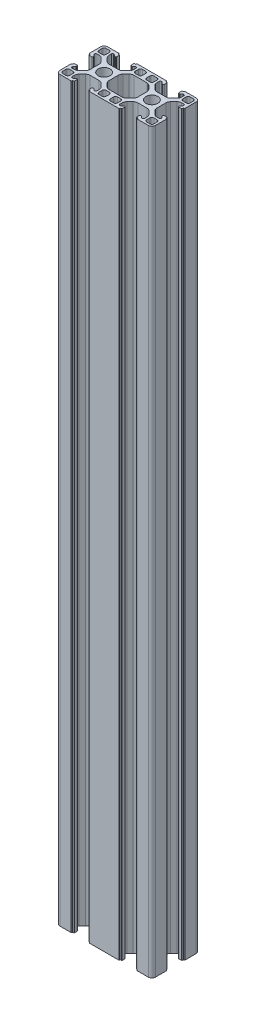
SolidWorks part; units mm, degrees
ref_plane "Спереди" through (0, 0, 0) normal (0, 0, 1) x (1, 0, 0)
ref_plane "Сверху" through (0, 0, 0) normal (0, 1, 0) x (1, 0, 0)
ref_plane "Справа" through (0, 0, 0) normal (1, 0, 0) x (0, 0, -1)
sketch "Эскиз1" plane through (0, 0, 0) normal (0, 1, 0) x (1, 0, 0)
  line L0 (-3.1522, 8.2837) -> (-1.6522, 6.7837) construction
  line L1 (18.3478, 9.7837) -> (15.3478, 6.7837) construction
  line L2 (-10.7522, 0.6837) -> (-0.7522, 10.6837) construction
  line L3 (9.2478, 4.6837) -> (11.1466, 4.6837)
  line L4 (9.2478, 0.6837) -> (19.2478, 10.6837) construction
  line L5 (16.8478, 8.2837) -> (15.3478, 9.7837) construction
  line L6 (12.5608, 5.2695) -> (13.862, 6.5707)
  line L7 (16.1478, 6.7837) -> (17.5478, 6.7837)
  line L8 (15.3478, 7.5837) -> (15.3478, 8.9837)
  line L9 (17.5478, 9.7837) -> (16.1478, 9.7837)
  line L10 (14.4478, 8.8837) -> (14.4478, 7.9849)
  line L11 (13.011, 8.757) -> (13.4914, 9.2373)
  line L12 (12.4478, 10.2328) -> (12.9478, 10.2328)
  line L13 (12.8343, 8.6837) -> (12.5478, 8.6837)
  line L14 (13.8449, 9.3837) -> (13.9478, 9.3837)
  line L15 (12.9478, 10.5337) -> (12.9478, 10.2328)
  line L16 (12.2978, 10.0828) -> (12.2978, 8.9337)
  line L17 (17.7478, 10.6837) -> (13.0978, 10.6837)
  line L18 (18.3478, 8.9837) -> (18.3478, 7.5837)
  line L19 (19.2478, 9.1837) -> (19.2478, 4.5337)
  line L20 (18.6469, 3.7337) -> (17.4978, 3.7337)
  line L21 (19.0978, 4.3837) -> (18.7969, 4.3837)
  line L22 (17.9478, 5.2808) -> (17.9478, 5.3837)
  line L23 (17.2478, 4.2702) -> (17.2478, 3.9837)
  line L24 (18.7969, 3.8837) -> (18.7969, 4.3837)
  line L25 (17.321, 4.447) -> (17.8014, 4.9273)
  line L26 (17.4478, 5.8837) -> (16.549, 5.8837)
  line L27 (13.8336, 3.9967) -> (15.1348, 5.2979)
  line L28 (13.2478, 0.6837) -> (13.2478, 2.5825)
  line L29 (13.2478, 0.6837) -> (13.2478, -1.2151)
  line L30 (13.8336, -2.6293) -> (15.1348, -3.9305)
  line L31 (15.3478, -6.2163) -> (15.3478, -7.6163)
  line L32 (16.1478, -5.4163) -> (17.5478, -5.4163)
  line L33 (18.3478, -7.6163) -> (18.3478, -6.2163)
  line L34 (17.4478, -4.5163) -> (16.549, -4.5163)
  line L35 (17.321, -3.0795) -> (17.8014, -3.5598)
  line L36 (18.7969, -2.5163) -> (18.7969, -3.0163)
  line L37 (17.2478, -2.9027) -> (17.2478, -2.6163)
  line L38 (17.9478, -3.9134) -> (17.9478, -4.0163)
  line L39 (19.0978, -3.0163) -> (18.7969, -3.0163)
  line L40 (18.6469, -2.3663) -> (17.4978, -2.3663)
  line L41 (19.2478, -7.8163) -> (19.2478, -3.1663)
  line L42 (17.5478, -8.4163) -> (16.1478, -8.4163)
  line L43 (17.7478, -9.3163) -> (13.0978, -9.3163)
  line L44 (12.2978, -8.7153) -> (12.2978, -7.5663)
  line L45 (12.9478, -9.1663) -> (12.9478, -8.8653)
  line L46 (13.8449, -8.0163) -> (13.9478, -8.0163)
  line L47 (12.8343, -7.3163) -> (12.5478, -7.3163)
  line L48 (12.4478, -8.8653) -> (12.9478, -8.8653)
  line L49 (13.011, -7.3895) -> (13.4914, -7.8698)
  line L50 (14.4478, -7.5163) -> (14.4478, -6.6175)
  line L51 (12.5608, -3.9021) -> (13.862, -5.2033)
  line L52 (9.2478, -3.3163) -> (11.1466, -3.3163)
  line L53 (18.3478, -8.4163) -> (15.3478, -5.4163) construction
  line L54 (9.2478, 0.6837) -> (19.2478, -9.3163) construction
  line L55 (16.8478, -6.9163) -> (18.3478, -5.4163) construction
  line L56 (9.2478, -3.3163) -> (7.349, -3.3163)
  line L57 (5.9348, -3.9021) -> (4.6336, -5.2033)
  line L58 (2.3478, -5.4163) -> (0.9478, -5.4163)
  line L59 (3.1478, -6.2163) -> (3.1478, -7.6163)
  line L60 (0.9478, -8.4163) -> (2.3478, -8.4163)
  line L61 (4.0478, -7.5163) -> (4.0478, -6.6175)
  line L62 (5.4846, -7.3895) -> (5.0043, -7.8698)
  line L63 (6.0478, -8.8653) -> (5.5478, -8.8653)
  line L64 (5.6614, -7.3163) -> (5.9478, -7.3163)
  line L65 (4.6507, -8.0163) -> (4.5478, -8.0163)
  line L66 (5.5478, -9.1663) -> (5.5478, -8.8653)
  line L67 (6.1978, -8.7153) -> (6.1978, -7.5663)
  line L68 (0.7478, -9.3163) -> (5.3978, -9.3163)
  line L69 (0.1478, -7.6163) -> (0.1478, -6.2163)
  line L70 (1.0478, -4.5163) -> (1.9466, -4.5163)
  line L71 (4.662, -2.6293) -> (3.3608, -3.9305)
  line L72 (5.2478, 0.6837) -> (5.2478, -1.2151)
  line L73 (-1.6522, 9.7837) -> (-4.6522, 6.7837) construction
  line L74 (0.1478, -8.4163) -> (3.1478, -5.4163) construction
  line L75 (-3.1522, -6.9163) -> (-4.6522, -8.4163) construction
  line L76 (9.2478, 0.6837) -> (-0.7522, -9.3163) construction
  line L77 (1.6478, -6.9163) -> (3.1478, -8.4163) construction
  line L78 (5.2478, 0.6837) -> (5.2478, 2.5825)
  line L79 (4.662, 3.9967) -> (3.3608, 5.2979)
  line L80 (3.1478, 7.5837) -> (3.1478, 8.9837)
  line L81 (2.3478, 6.7837) -> (0.9478, 6.7837)
  line L82 (0.1478, 8.9837) -> (0.1478, 7.5837)
  line L83 (1.0478, 5.8837) -> (1.9466, 5.8837)
  line L84 (0.9478, 9.7837) -> (2.3478, 9.7837)
  line L85 (0.7478, 10.6837) -> (5.3978, 10.6837)
  line L86 (6.1978, 10.0828) -> (6.1978, 8.9337)
  line L87 (5.5478, 10.5337) -> (5.5478, 10.2328)
  line L88 (4.6507, 9.3837) -> (4.5478, 9.3837)
  line L89 (5.6614, 8.6837) -> (5.9478, 8.6837)
  line L90 (6.0478, 10.2328) -> (5.5478, 10.2328)
  line L91 (5.4846, 8.757) -> (5.0043, 9.2373)
  line L92 (4.0478, 8.8837) -> (4.0478, 7.9849)
  line L93 (5.9348, 5.2695) -> (4.6336, 6.5707)
  line L94 (9.2478, 4.6837) -> (7.349, 4.6837)
  line L95 (-2.5162, 0.6837) -> (20.7522, 0.6837) construction
  line L96 (0.1478, 9.7837) -> (3.1478, 6.7837) construction
  line L97 (9.2478, -11.4027) -> (9.2478, 11.4027) construction
  line L98 (9.2478, 0.6837) -> (-0.7522, 10.6837) construction
  line L99 (1.6478, 8.2837) -> (0.1478, 6.7837) construction
  line L100 (-10.7522, 0.6837) -> (-0.7522, -9.3163) construction
  line L101 (-1.6522, -8.4163) -> (-4.6522, -5.4163) construction
  line L102 (-18.3522, -6.9163) -> (-19.8522, -5.4163) construction
  line L103 (-10.7522, 0.6837) -> (-20.7522, -9.3163) construction
  line L104 (-19.8522, -8.4163) -> (-16.8522, -5.4163) construction
  line L105 (-18.3522, 8.2837) -> (-16.8522, 9.7837) construction
  line L106 (-10.7522, 0.6837) -> (-20.7522, 10.6837) construction
  line L107 (-19.8522, 9.7837) -> (-16.8522, 6.7837) construction
  line L108 (-10.7522, 4.6837) -> (-8.8534, 4.6837)
  line L109 (-7.4392, 5.2695) -> (-6.138, 6.5707)
  line L110 (-5.5522, 8.8837) -> (-5.5522, 7.9849)
  line L111 (-6.989, 8.757) -> (-6.5086, 9.2373)
  line L112 (-7.5522, 10.2328) -> (-7.0522, 10.2328)
  line L113 (-7.1657, 8.6837) -> (-7.4522, 8.6837)
  line L114 (-6.1551, 9.3837) -> (-6.0522, 9.3837)
  line L115 (-7.0522, 10.5337) -> (-7.0522, 10.2328)
  line L116 (-7.7022, 10.0828) -> (-7.7022, 8.9337)
  line L117 (-2.2522, 10.6837) -> (-6.9022, 10.6837)
  line L118 (-2.4522, 9.7837) -> (-3.8522, 9.7837)
  line L119 (-2.5522, 5.8837) -> (-3.451, 5.8837)
  line L120 (-1.6522, 8.9837) -> (-1.6522, 7.5837)
  line L121 (-3.8522, 6.7837) -> (-2.4522, 6.7837)
  line L122 (-4.6522, 7.5837) -> (-4.6522, 8.9837)
  line L123 (-6.1664, 3.9967) -> (-4.8652, 5.2979)
  line L124 (-6.7522, 0.6837) -> (-6.7522, 2.5825)
  line L125 (-6.7522, 0.6837) -> (-6.7522, -1.2151)
  line L126 (-6.1664, -2.6293) -> (-4.8652, -3.9305)
  line L127 (-2.5522, -4.5163) -> (-3.451, -4.5163)
  line L128 (-1.6522, -7.6163) -> (-1.6522, -6.2163)
  line L129 (-2.2522, -9.3163) -> (-6.9022, -9.3163)
  line L130 (-7.7022, -8.7153) -> (-7.7022, -7.5663)
  line L131 (-7.0522, -9.1663) -> (-7.0522, -8.8653)
  line L132 (-6.1551, -8.0163) -> (-6.0522, -8.0163)
  line L133 (-7.1657, -7.3163) -> (-7.4522, -7.3163)
  line L134 (-7.5522, -8.8653) -> (-7.0522, -8.8653)
  line L135 (-6.989, -7.3895) -> (-6.5086, -7.8698)
  line L136 (-5.5522, -7.5163) -> (-5.5522, -6.6175)
  line L137 (-2.4522, -8.4163) -> (-3.8522, -8.4163)
  line L138 (-4.6522, -6.2163) -> (-4.6522, -7.6163)
  line L139 (-3.8522, -5.4163) -> (-2.4522, -5.4163)
  line L140 (-7.4392, -3.9021) -> (-6.138, -5.2033)
  line L141 (-10.7522, -3.3163) -> (-8.8534, -3.3163)
  line L142 (-10.7522, -3.3163) -> (-12.651, -3.3163)
  line L143 (-14.0652, -3.9021) -> (-15.3664, -5.2033)
  line L144 (-15.9522, -7.5163) -> (-15.9522, -6.6175)
  line L145 (-14.5154, -7.3895) -> (-14.9957, -7.8698)
  line L146 (-13.9522, -8.8653) -> (-14.4522, -8.8653)
  line L147 (-14.3386, -7.3163) -> (-14.0522, -7.3163)
  line L148 (-15.3493, -8.0163) -> (-15.4522, -8.0163)
  line L149 (-14.4522, -9.1663) -> (-14.4522, -8.8653)
  line L150 (-13.8022, -8.7153) -> (-13.8022, -7.5663)
  line L151 (-19.2522, -9.3163) -> (-14.6022, -9.3163)
  line L152 (-19.0522, -8.4163) -> (-17.6522, -8.4163)
  line L153 (-20.7522, -7.8163) -> (-20.7522, -3.1663)
  line L154 (-20.1512, -2.3663) -> (-19.0022, -2.3663)
  line L155 (-20.6022, -3.0163) -> (-20.3012, -3.0163)
  line L156 (-19.4522, -3.9134) -> (-19.4522, -4.0163)
  line L157 (-18.7522, -2.9027) -> (-18.7522, -2.6163)
  line L158 (-20.3012, -2.5163) -> (-20.3012, -3.0163)
  line L159 (-18.8254, -3.0795) -> (-19.3057, -3.5598)
  line L160 (-18.9522, -4.5163) -> (-18.0534, -4.5163)
  line L161 (-19.8522, -7.6163) -> (-19.8522, -6.2163)
  line L162 (-17.6522, -5.4163) -> (-19.0522, -5.4163)
  line L163 (-16.8522, -6.2163) -> (-16.8522, -7.6163)
  line L164 (-15.338, -2.6293) -> (-16.6392, -3.9305)
  line L165 (-14.7522, 0.6837) -> (-14.7522, -1.2151)
  line L166 (-14.7522, 0.6837) -> (-14.7522, 2.5825)
  line L167 (-15.338, 3.9967) -> (-16.6392, 5.2979)
  line L168 (-18.9522, 5.8837) -> (-18.0534, 5.8837)
  line L169 (-18.8254, 4.447) -> (-19.3057, 4.9273)
  line L170 (-20.3012, 3.8837) -> (-20.3012, 4.3837)
  line L171 (-18.7522, 4.2702) -> (-18.7522, 3.9837)
  line L172 (-19.4522, 5.2808) -> (-19.4522, 5.3837)
  line L173 (-20.6022, 4.3837) -> (-20.3012, 4.3837)
  line L174 (-20.1512, 3.7337) -> (-19.0022, 3.7337)
  line L175 (-20.7522, 9.1837) -> (-20.7522, 4.5337)
  line L176 (-19.8522, 8.9837) -> (-19.8522, 7.5837)
  line L177 (-19.2522, 10.6837) -> (-14.6022, 10.6837)
  line L178 (-13.8022, 10.0828) -> (-13.8022, 8.9337)
  line L179 (-14.4522, 10.5337) -> (-14.4522, 10.2328)
  line L180 (-15.3493, 9.3837) -> (-15.4522, 9.3837)
  line L181 (-14.3386, 8.6837) -> (-14.0522, 8.6837)
  line L182 (-13.9522, 10.2328) -> (-14.4522, 10.2328)
  line L183 (-14.5154, 8.757) -> (-14.9957, 9.2373)
  line L184 (-15.9522, 8.8837) -> (-15.9522, 7.9849)
  line L185 (-19.0522, 9.7837) -> (-17.6522, 9.7837)
  line L186 (-16.8522, 7.5837) -> (-16.8522, 8.9837)
  line L187 (-17.6522, 6.7837) -> (-19.0522, 6.7837)
  line L188 (-14.0652, 5.2695) -> (-15.3664, 6.5707)
  line L189 (-10.7522, 4.6837) -> (-12.651, 4.6837)
  line L190 (-2.2522, -9.3163) -> (0.7478, -9.3163)
  line L191 (-2.5522, -4.5163) -> (1.0478, -4.5163)
  line L192 (-2.5522, 5.8837) -> (1.0478, 5.8837)
  line L193 (-2.2522, 10.6837) -> (0.7478, 10.6837)
  arc A0 (18.3478, 8.9837) -> (17.5478, 9.7837) centre (17.5478, 8.9837) ccw
  arc A1 (16.1478, 9.7837) -> (15.3478, 8.9837) centre (16.1478, 8.9837) ccw
  arc A2 (16.1478, 6.7837) -> (15.3478, 7.5837) centre (16.1478, 7.5837) cw
  arc A3 (17.7478, 10.6837) -> (19.2478, 9.1837) centre (17.7478, 9.1837) cw
  arc A4 (12.4478, 10.2328) -> (12.2978, 10.0828) centre (12.4478, 10.0828) ccw
  arc A5 (13.0978, 10.6837) -> (12.9478, 10.5337) centre (13.0978, 10.5337) ccw
  arc A6 (12.8343, 8.6837) -> (13.011, 8.757) centre (12.8343, 8.9337) ccw
  arc A7 (12.5478, 8.6837) -> (12.2978, 8.9337) centre (12.5478, 8.9337) cw
  arc A8 (13.4914, 9.2373) -> (13.8449, 9.3837) centre (13.8449, 8.8837) cw
  arc A9 (13.9478, 9.3837) -> (14.4478, 8.8837) centre (13.9478, 8.8837) cw
  arc A10 (11.7478, 0.6837) -> (9.2478, 3.1837) centre (9.2478, 0.6837) ccw
  arc A11 (11.1466, 4.6837) -> (12.5608, 5.2695) centre (11.1466, 6.6837) ccw
  arc A12 (14.4478, 7.9849) -> (13.862, 6.5707) centre (12.4478, 7.9849) cw
  arc A13 (18.3478, 7.5837) -> (17.5478, 6.7837) centre (17.5478, 7.5837) cw
  arc A14 (17.9478, 5.3837) -> (17.4478, 5.8837) centre (17.4478, 5.3837) ccw
  arc A15 (17.8014, 4.9273) -> (17.9478, 5.2808) centre (17.4478, 5.2808) ccw
  arc A16 (17.2478, 3.9837) -> (17.4978, 3.7337) centre (17.4978, 3.9837) ccw
  arc A17 (17.2478, 4.2702) -> (17.321, 4.447) centre (17.4978, 4.2702) cw
  arc A18 (19.2478, 4.5337) -> (19.0978, 4.3837) centre (19.0978, 4.5337) cw
  arc A19 (18.7969, 3.8837) -> (18.6469, 3.7337) centre (18.6469, 3.8837) cw
  arc A20 (16.549, 5.8837) -> (15.1348, 5.2979) centre (16.549, 3.8837) ccw
  arc A21 (13.2478, 2.5825) -> (13.8336, 3.9967) centre (15.2478, 2.5825) cw
  arc A22 (17.5478, -8.4163) -> (18.3478, -7.6163) centre (17.5478, -7.6163) ccw
  arc A23 (18.3478, -6.2163) -> (17.5478, -5.4163) centre (17.5478, -6.2163) ccw
  arc A24 (15.3478, -6.2163) -> (16.1478, -5.4163) centre (16.1478, -6.2163) cw
  arc A25 (19.2478, -7.8163) -> (17.7478, -9.3163) centre (17.7478, -7.8163) cw
  arc A26 (18.7969, -2.5163) -> (18.6469, -2.3663) centre (18.6469, -2.5163) ccw
  arc A27 (19.2478, -3.1663) -> (19.0978, -3.0163) centre (19.0978, -3.1663) ccw
  arc A28 (17.2478, -2.9027) -> (17.321, -3.0795) centre (17.4978, -2.9027) ccw
  arc A29 (17.2478, -2.6163) -> (17.4978, -2.3663) centre (17.4978, -2.6163) cw
  arc A30 (17.8014, -3.5598) -> (17.9478, -3.9134) centre (17.4478, -3.9134) cw
  arc A31 (17.9478, -4.0163) -> (17.4478, -4.5163) centre (17.4478, -4.0163) cw
  arc A32 (9.2478, -1.8163) -> (11.7478, 0.6837) centre (9.2478, 0.6837) ccw
  arc A33 (13.2478, -1.2151) -> (13.8336, -2.6293) centre (15.2478, -1.2151) ccw
  arc A34 (16.549, -4.5163) -> (15.1348, -3.9305) centre (16.549, -2.5163) cw
  arc A35 (16.1478, -8.4163) -> (15.3478, -7.6163) centre (16.1478, -7.6163) cw
  arc A36 (13.9478, -8.0163) -> (14.4478, -7.5163) centre (13.9478, -7.5163) ccw
  arc A37 (13.4914, -7.8698) -> (13.8449, -8.0163) centre (13.8449, -7.5163) ccw
  arc A38 (12.5478, -7.3163) -> (12.2978, -7.5663) centre (12.5478, -7.5663) ccw
  arc A39 (12.8343, -7.3163) -> (13.011, -7.3895) centre (12.8343, -7.5663) cw
  arc A40 (13.0978, -9.3163) -> (12.9478, -9.1663) centre (13.0978, -9.1663) cw
  arc A41 (12.4478, -8.8653) -> (12.2978, -8.7153) centre (12.4478, -8.7153) cw
  arc A42 (14.4478, -6.6175) -> (13.862, -5.2033) centre (12.4478, -6.6175) ccw
  arc A43 (11.1466, -3.3163) -> (12.5608, -3.9021) centre (11.1466, -5.3163) cw
  arc A44 (0.1478, -7.6163) -> (0.9478, -8.4163) centre (0.9478, -7.6163) ccw
  arc A45 (2.3478, -8.4163) -> (3.1478, -7.6163) centre (2.3478, -7.6163) ccw
  arc A46 (2.3478, -5.4163) -> (3.1478, -6.2163) centre (2.3478, -6.2163) cw
  arc A47 (6.0478, -8.8653) -> (6.1978, -8.7153) centre (6.0478, -8.7153) ccw
  arc A48 (5.3978, -9.3163) -> (5.5478, -9.1663) centre (5.3978, -9.1663) ccw
  arc A49 (5.6614, -7.3163) -> (5.4846, -7.3895) centre (5.6614, -7.5663) ccw
  arc A50 (5.9478, -7.3163) -> (6.1978, -7.5663) centre (5.9478, -7.5663) cw
  arc A51 (5.0043, -7.8698) -> (4.6507, -8.0163) centre (4.6507, -7.5163) cw
  arc A52 (4.5478, -8.0163) -> (4.0478, -7.5163) centre (4.5478, -7.5163) cw
  arc A53 (6.7478, 0.6837) -> (9.2478, -1.8163) centre (9.2478, 0.6837) ccw
  arc A54 (7.349, -3.3163) -> (5.9348, -3.9021) centre (7.349, -5.3163) ccw
  arc A55 (4.0478, -6.6175) -> (4.6336, -5.2033) centre (6.0478, -6.6175) cw
  arc A56 (0.1478, -6.2163) -> (0.9478, -5.4163) centre (0.9478, -6.2163) cw
  arc A57 (1.9466, -4.5163) -> (3.3608, -3.9305) centre (1.9466, -2.5163) ccw
  arc A58 (5.2478, -1.2151) -> (4.662, -2.6293) centre (3.2478, -1.2151) cw
  arc A59 (0.9478, 9.7837) -> (0.1478, 8.9837) centre (0.9478, 8.9837) ccw
  arc A60 (0.1478, 7.5837) -> (0.9478, 6.7837) centre (0.9478, 7.5837) ccw
  arc A61 (3.1478, 7.5837) -> (2.3478, 6.7837) centre (2.3478, 7.5837) cw
  arc A62 (9.2478, 3.1837) -> (6.7478, 0.6837) centre (9.2478, 0.6837) ccw
  arc A63 (5.2478, 2.5825) -> (4.662, 3.9967) centre (3.2478, 2.5825) ccw
  arc A64 (1.9466, 5.8837) -> (3.3608, 5.2979) centre (1.9466, 3.8837) cw
  arc A65 (2.3478, 9.7837) -> (3.1478, 8.9837) centre (2.3478, 8.9837) cw
  arc A66 (4.5478, 9.3837) -> (4.0478, 8.8837) centre (4.5478, 8.8837) ccw
  arc A67 (5.0043, 9.2373) -> (4.6507, 9.3837) centre (4.6507, 8.8837) ccw
  arc A68 (5.9478, 8.6837) -> (6.1978, 8.9337) centre (5.9478, 8.9337) ccw
  arc A69 (5.6614, 8.6837) -> (5.4846, 8.757) centre (5.6614, 8.9337) cw
  arc A70 (5.3978, 10.6837) -> (5.5478, 10.5337) centre (5.3978, 10.5337) cw
  arc A71 (6.0478, 10.2328) -> (6.1978, 10.0828) centre (6.0478, 10.0828) cw
  arc A72 (4.0478, 7.9849) -> (4.6336, 6.5707) centre (6.0478, 7.9849) ccw
  arc A73 (7.349, 4.6837) -> (5.9348, 5.2695) centre (7.349, 6.6837) cw
  arc A74 (-8.8534, 4.6837) -> (-7.4392, 5.2695) centre (-8.8534, 6.6837) ccw
  arc A75 (-5.5522, 7.9849) -> (-6.138, 6.5707) centre (-7.5522, 7.9849) cw
  arc A76 (-7.5522, 10.2328) -> (-7.7022, 10.0828) centre (-7.5522, 10.0828) ccw
  arc A77 (-6.9022, 10.6837) -> (-7.0522, 10.5337) centre (-6.9022, 10.5337) ccw
  arc A78 (-7.1657, 8.6837) -> (-6.989, 8.757) centre (-7.1657, 8.9337) ccw
  arc A79 (-7.4522, 8.6837) -> (-7.7022, 8.9337) centre (-7.4522, 8.9337) cw
  arc A80 (-6.5086, 9.2373) -> (-6.1551, 9.3837) centre (-6.1551, 8.8837) cw
  arc A81 (-6.0522, 9.3837) -> (-5.5522, 8.8837) centre (-6.0522, 8.8837) cw
  arc A82 (-3.8522, 9.7837) -> (-4.6522, 8.9837) centre (-3.8522, 8.9837) ccw
  arc A83 (-3.451, 5.8837) -> (-4.8652, 5.2979) centre (-3.451, 3.8837) ccw
  arc A84 (-6.7522, 2.5825) -> (-6.1664, 3.9967) centre (-4.7522, 2.5825) cw
  arc A85 (-10.7522, 3.1837) -> (-8.2522, 0.6837) centre (-10.7522, 0.6837) cw
  arc A86 (-4.6522, 7.5837) -> (-3.8522, 6.7837) centre (-3.8522, 7.5837) ccw
  arc A87 (-1.6522, 7.5837) -> (-2.4522, 6.7837) centre (-2.4522, 7.5837) cw
  arc A88 (-2.4522, 9.7837) -> (-1.6522, 8.9837) centre (-2.4522, 8.9837) cw
  arc A89 (-6.7522, -1.2151) -> (-6.1664, -2.6293) centre (-4.7522, -1.2151) ccw
  arc A90 (-3.451, -4.5163) -> (-4.8652, -3.9305) centre (-3.451, -2.5163) cw
  arc A91 (-1.6522, -6.2163) -> (-2.4522, -5.4163) centre (-2.4522, -6.2163) ccw
  arc A92 (-5.5522, -6.6175) -> (-6.138, -5.2033) centre (-7.5522, -6.6175) ccw
  arc A93 (-8.8534, -3.3163) -> (-7.4392, -3.9021) centre (-8.8534, -5.3163) cw
  arc A94 (-8.2522, 0.6837) -> (-10.7522, -1.8163) centre (-10.7522, 0.6837) cw
  arc A95 (-6.0522, -8.0163) -> (-5.5522, -7.5163) centre (-6.0522, -7.5163) ccw
  arc A96 (-6.5086, -7.8698) -> (-6.1551, -8.0163) centre (-6.1551, -7.5163) ccw
  arc A97 (-7.4522, -7.3163) -> (-7.7022, -7.5663) centre (-7.4522, -7.5663) ccw
  arc A98 (-7.1657, -7.3163) -> (-6.989, -7.3895) centre (-7.1657, -7.5663) cw
  arc A99 (-6.9022, -9.3163) -> (-7.0522, -9.1663) centre (-6.9022, -9.1663) cw
  arc A100 (-7.5522, -8.8653) -> (-7.7022, -8.7153) centre (-7.5522, -8.7153) cw
  arc A101 (-3.8522, -5.4163) -> (-4.6522, -6.2163) centre (-3.8522, -6.2163) ccw
  arc A102 (-3.8522, -8.4163) -> (-4.6522, -7.6163) centre (-3.8522, -7.6163) cw
  arc A103 (-1.6522, -7.6163) -> (-2.4522, -8.4163) centre (-2.4522, -7.6163) cw
  arc A104 (-12.651, -3.3163) -> (-14.0652, -3.9021) centre (-12.651, -5.3163) ccw
  arc A105 (-15.9522, -6.6175) -> (-15.3664, -5.2033) centre (-13.9522, -6.6175) cw
  arc A106 (-13.9522, -8.8653) -> (-13.8022, -8.7153) centre (-13.9522, -8.7153) ccw
  arc A107 (-14.6022, -9.3163) -> (-14.4522, -9.1663) centre (-14.6022, -9.1663) ccw
  arc A108 (-14.3386, -7.3163) -> (-14.5154, -7.3895) centre (-14.3386, -7.5663) ccw
  arc A109 (-14.0522, -7.3163) -> (-13.8022, -7.5663) centre (-14.0522, -7.5663) cw
  arc A110 (-14.9957, -7.8698) -> (-15.3493, -8.0163) centre (-15.3493, -7.5163) cw
  arc A111 (-15.4522, -8.0163) -> (-15.9522, -7.5163) centre (-15.4522, -7.5163) cw
  arc A112 (-17.6522, -8.4163) -> (-16.8522, -7.6163) centre (-17.6522, -7.6163) ccw
  arc A113 (-18.0534, -4.5163) -> (-16.6392, -3.9305) centre (-18.0534, -2.5163) ccw
  arc A114 (-14.7522, -1.2151) -> (-15.338, -2.6293) centre (-16.7522, -1.2151) cw
  arc A115 (-10.7522, -1.8163) -> (-13.2522, 0.6837) centre (-10.7522, 0.6837) cw
  arc A116 (-19.4522, -4.0163) -> (-18.9522, -4.5163) centre (-18.9522, -4.0163) ccw
  arc A117 (-19.3057, -3.5598) -> (-19.4522, -3.9134) centre (-18.9522, -3.9134) ccw
  arc A118 (-18.7522, -2.6163) -> (-19.0022, -2.3663) centre (-19.0022, -2.6163) ccw
  arc A119 (-18.7522, -2.9027) -> (-18.8254, -3.0795) centre (-19.0022, -2.9027) cw
  arc A120 (-20.7522, -3.1663) -> (-20.6022, -3.0163) centre (-20.6022, -3.1663) cw
  arc A121 (-20.3012, -2.5163) -> (-20.1512, -2.3663) centre (-20.1512, -2.5163) cw
  arc A122 (-20.7522, -7.8163) -> (-19.2522, -9.3163) centre (-19.2522, -7.8163) ccw
  arc A123 (-16.8522, -6.2163) -> (-17.6522, -5.4163) centre (-17.6522, -6.2163) ccw
  arc A124 (-19.8522, -6.2163) -> (-19.0522, -5.4163) centre (-19.0522, -6.2163) cw
  arc A125 (-19.0522, -8.4163) -> (-19.8522, -7.6163) centre (-19.0522, -7.6163) cw
  arc A126 (-14.7522, 2.5825) -> (-15.338, 3.9967) centre (-16.7522, 2.5825) ccw
  arc A127 (-18.0534, 5.8837) -> (-16.6392, 5.2979) centre (-18.0534, 3.8837) cw
  arc A128 (-20.3012, 3.8837) -> (-20.1512, 3.7337) centre (-20.1512, 3.8837) ccw
  arc A129 (-20.7522, 4.5337) -> (-20.6022, 4.3837) centre (-20.6022, 4.5337) ccw
  arc A130 (-18.7522, 4.2702) -> (-18.8254, 4.447) centre (-19.0022, 4.2702) ccw
  arc A131 (-18.7522, 3.9837) -> (-19.0022, 3.7337) centre (-19.0022, 3.9837) cw
  arc A132 (-19.3057, 4.9273) -> (-19.4522, 5.2808) centre (-18.9522, 5.2808) cw
  arc A133 (-19.4522, 5.3837) -> (-18.9522, 5.8837) centre (-18.9522, 5.3837) cw
  arc A134 (-19.8522, 7.5837) -> (-19.0522, 6.7837) centre (-19.0522, 7.5837) ccw
  arc A135 (-15.9522, 7.9849) -> (-15.3664, 6.5707) centre (-13.9522, 7.9849) ccw
  arc A136 (-12.651, 4.6837) -> (-14.0652, 5.2695) centre (-12.651, 6.6837) cw
  arc A137 (-13.2522, 0.6837) -> (-10.7522, 3.1837) centre (-10.7522, 0.6837) cw
  arc A138 (-15.4522, 9.3837) -> (-15.9522, 8.8837) centre (-15.4522, 8.8837) ccw
  arc A139 (-14.9957, 9.2373) -> (-15.3493, 9.3837) centre (-15.3493, 8.8837) ccw
  arc A140 (-14.0522, 8.6837) -> (-13.8022, 8.9337) centre (-14.0522, 8.9337) ccw
  arc A141 (-14.3386, 8.6837) -> (-14.5154, 8.757) centre (-14.3386, 8.9337) cw
  arc A142 (-14.6022, 10.6837) -> (-14.4522, 10.5337) centre (-14.6022, 10.5337) cw
  arc A143 (-13.9522, 10.2328) -> (-13.8022, 10.0828) centre (-13.9522, 10.0828) cw
  arc A144 (-19.2522, 10.6837) -> (-20.7522, 9.1837) centre (-19.2522, 9.1837) ccw
  arc A145 (-17.6522, 6.7837) -> (-16.8522, 7.5837) centre (-17.6522, 7.5837) ccw
  arc A146 (-17.6522, 9.7837) -> (-16.8522, 8.9837) centre (-17.6522, 8.9837) cw
  arc A147 (-19.8522, 8.9837) -> (-19.0522, 9.7837) centre (-19.0522, 8.9837) cw
  point P0 (9.2478, 0.6837)
  point P12 (9.2478, 0.6837)
  point P45 (17.9478, 4.3837)
  point P104 (12.9478, -8.0163)
  point P155 (12.9478, 9.3837)
  point P163 (17.9478, -3.0163)
  point P164 (9.2478, -3.2405)
  point P166 (9.2478, 0.6837)
  point P224 (5.5478, -8.0163)
  point P225 (5.3236, 0.6837)
  point P227 (9.2478, 0.6837)
  point P267 (5.5478, 9.3837)
  point P272 (13.1721, 0.6837)
  point P288 (9.2478, 4.608)
  point P290 (9.2478, 0.6837)
  point P515 (-10.7522, 4.608)
  point P516 (-14.6764, 0.6837)
  point P517 (-7.0522, 9.3837)
  point P518 (-6.8279, 0.6837)
  point P519 (-7.0522, -8.0163)
  point P520 (-10.7522, -3.2405)
  point P521 (-19.4522, -3.0163)
  point P522 (-14.4522, 9.3837)
  point P523 (-14.4522, -8.0163)
  point P524 (-19.4522, 4.3837)
extrude "Бобышка-Вытянуть1" add sketch "Эскиз1" along normal blind 309
